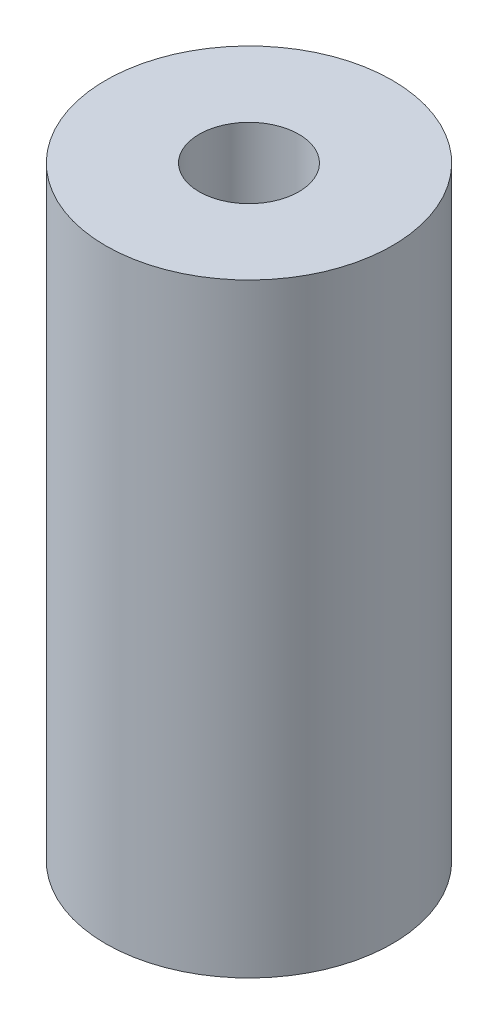
SolidWorks part; units mm, degrees
ref_plane "Front Plane" through (0, 0, 0) normal (0, 0, 1) x (1, 0, 0)
ref_plane "Top Plane" through (0, 0, 0) normal (0, 1, 0) x (1, 0, 0)
ref_plane "Right Plane" through (0, 0, 0) normal (1, 0, 0) x (0, 0, -1)
sketch "Sketch1" plane through (0, 0, 0) normal (0, 1, 0) x (1, 0, 0)
  circle A0 centre (0, 0) radius 4.6
  circle A1 centre (0, 0) radius 1.6
  dimension "D1" = 3.2
  dimension "D2" = 3
extrude "Boss-Extrude1" add sketch "Sketch1" along normal blind 19.4
